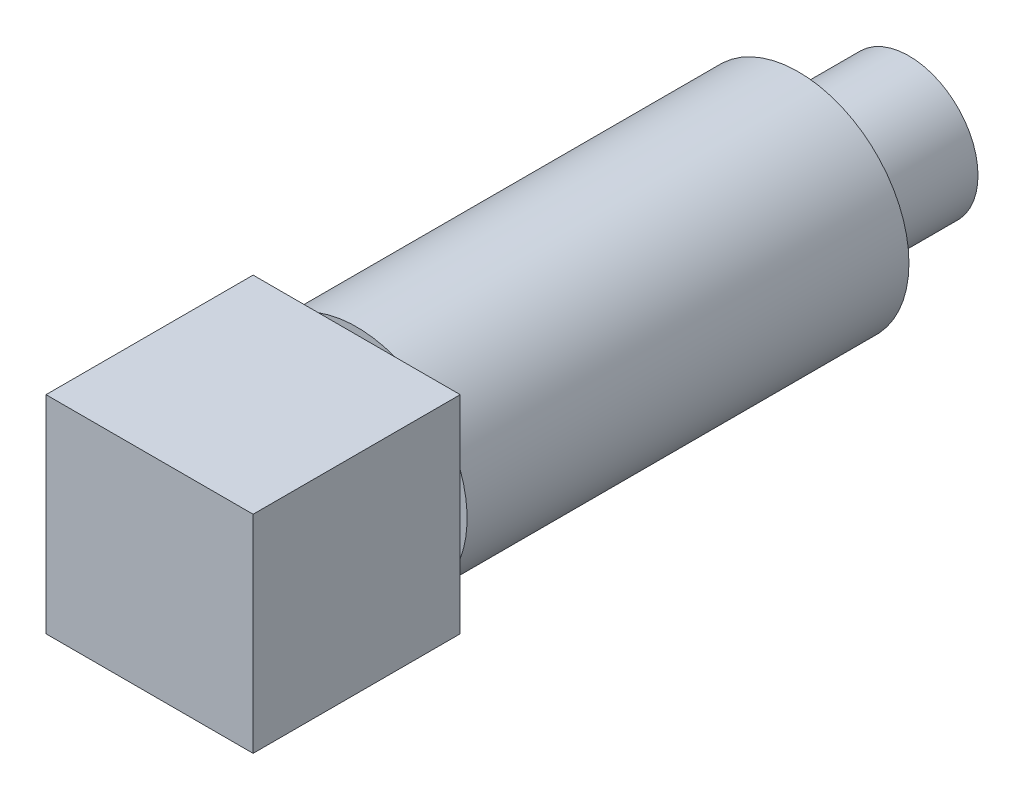
SolidWorks part; units mm, degrees
ref_plane "Front Plane" through (0, 0, 0) normal (0, 0, 1) x (1, 0, 0)
ref_plane "Top Plane" through (0, 0, 0) normal (0, 1, 0) x (1, 0, 0)
ref_plane "Right Plane" through (0, 0, 0) normal (1, 0, 0) x (0, 0, -1)
sketch "Sketch1" plane through (0, 0, 0) normal (0, 0, 1) x (1, 0, 0)
  circle A0 centre (0, 0) radius 5
  dimension "D1" = 10
extrude "Boss-Extrude1" add sketch "Sketch1" along normal blind 8
sketch "Sketch2" plane through (0, 0, 8) normal (0, 0, 1) x (1, 0, 0)
  circle A0 centre (0, 0) radius 8
  dimension "D1" = 16
extrude "Boss-Extrude2" add sketch "Sketch2" along normal blind 32
cosmetic thread "Cosmetic Thread1" parameters "D2"=13.797
sketch "Sketch3" plane through (0, 0, 40) normal (0, 0, 1) x (1, 0, 0)
  line L1 (7.5, 7.5) -> (-7.5, 7.5)
  line L2 (7.5, 7.5) -> (7.5, -7.5)
  line L3 (7.5, -7.5) -> (-7.5, -7.5)
  line L4 (-7.5, 7.5) -> (-7.5, -7.5)
  line L5 (7.5, 7.5) -> (-7.5, -7.5) construction
  line L6 (7.5, -7.5) -> (-7.5, 7.5) construction
  point P0 (0, 0)
  dimension "D1" = 15
  dimension "D2" = 15
extrude "Boss-Extrude3" add sketch "Sketch3" along normal blind 15
